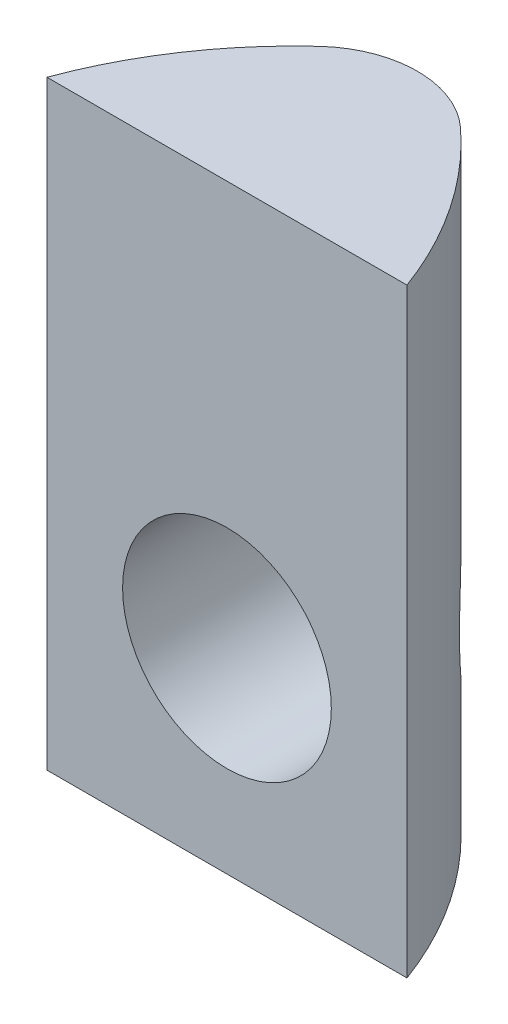
SolidWorks part; units mm, degrees
ref_plane "Front" through (0, 0, 0) normal (0, 0, 1) x (1, 0, 0)
ref_plane "Top" through (0, 0, 0) normal (0, 1, 0) x (1, 0, 0)
ref_plane "Right" through (0, 0, 0) normal (1, 0, 0) x (0, 0, -1)
ref_plane "Plane1" through (0, -7.5, 0) normal (0, -1, 0) x (1, 0, 0)
sketch "Sketch1" plane through (0, -7.5, 0) normal (0, -1, 0) x (1, 0, 0)
  line L0 (6.9, 0) -> (-6.9, 0)
  arc A0 (-6.9, 0) -> (0, -8.247) centre (8.1088, 5.5474) ccw
  arc A1 (0, -8.247) -> (6.9, 0) centre (-8.1088, 5.5474) ccw
extrude "Boss-Extrude1" add sketch "Sketch1" against normal blind 23
hole_wizard "Ø8.0 (8) Diameter Hole1" positions "Sketch3" profile "Sketch2" hole size "Ø8.0" standard "ANSI Metric"
sketch "Sketch3" plane through (0, 0, 0) normal (0, 0, 1) x (1, 0, 0)
  point P0 (0, 0)
sketch "Sketch2" plane through (0, 0, 0) normal (1, 0, 0) x (0, -1, 0)
  line L0 (0, 0) -> (0, 8.247)
  line L1 (0, 8.247) -> (4, 8.247)
  line L2 (4, 8.247) -> (4, 0)
  line L5 (4, 0) -> (0, 0)
  line L11 (0, -6.35) -> (0, 107.95) construction
  dimension "Thru Hole Dia." = 8
  dimension "Thru Hole Depth" = 8.247
fillet "Fillet1" radius 4 2 edges at (0, 9.75, -8.247) (0, -5.75, -8.247)
